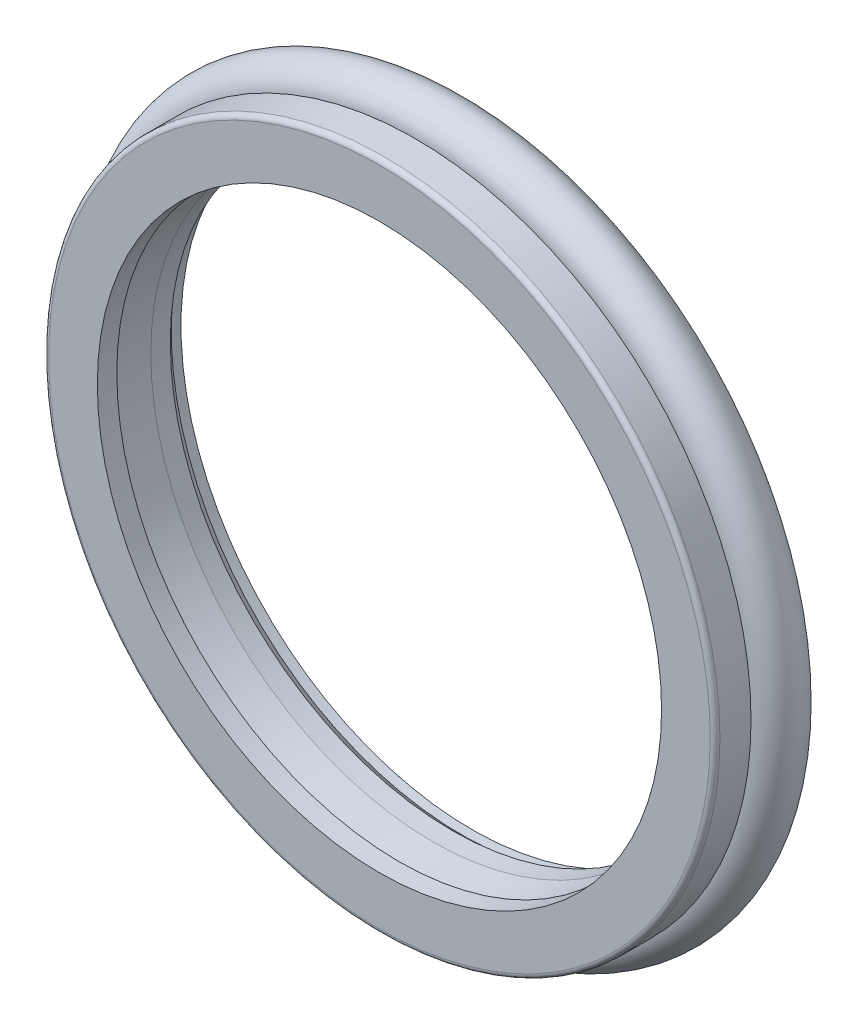
SolidWorks part; units mm, degrees
material "PTFE+NBR"
ref_plane "Front Plane" through (0, 0, 0) normal (0, 0, 1) x (1, 0, 0)
ref_plane "Top Plane" through (0, 0, 0) normal (0, 1, 0) x (1, 0, 0)
ref_plane "Right Plane" through (0, 0, 0) normal (1, 0, 0) x (0, 0, -1)
sketch "Sketch1" plane through (0, 0, 0) normal (1, 0, 0) x (0, 0, -1)
  line L0 (0, 0) -> (11.2675, 0) construction
  line L1 (0.25, 17.25) -> (1.85, 17.25)
  line L2 (0, 17) -> (0, 14.5)
  line L3 (4.75, 15.75) -> (4.75, 14.95)
  line L4 (4.75, 14.95) -> (4.25, 14.95)
  line L5 (4.25, 14.95) -> (3.75, 14.5)
  line L6 (1, 14.7) -> (2.75, 14.5)
  line L7 (4.75, 15.75) -> (1.85, 15.75)
  line L8 (1.85, 15.75) -> (1.85, 17.25)
  line L9 (1, 14.7) -> (1, 14.5)
  line L10 (1, 14.5) -> (0, 14.5)
  line L11 (3.75, 14.5) -> (2.75, 14.5)
  arc A2 (0.25, 17.25) -> (0, 17) centre (0.25, 17) ccw
  circle A4 centre (3.3, 17.05) radius 1.3 construction
  point P8 (3.3, 15.75)
  dimension "D8" = 1
  dimension "D12" = 36.7
  dimension "D13" = 2.6
  dimension "D14" = 31.5
  dimension "D16" = 2.9
  dimension "D17" = 0.25
  dimension "D1" = 0.5
  dimension "D2" = 1
  dimension "D3" = 4.75
  dimension "D4" = 1
  dimension "D5" = 34.5
  dimension "D6" = 29
  dimension "D7" = 0.8
  dimension "D9" = 29
  dimension "D10" = 0.2
revolve "Revolve1" add sketch "Sketch1" angle 360 about L0
sketch "Sketch2" plane through (0, 0, 0) normal (1, 0, 0) x (0, 0, -1)
  line L2 (0, 0) -> (10.3771, 0) construction
  circle A0 centre (3.3, 17.05) radius 1.3
  dimension "D1" = 2.6
  dimension "D2" = 36.7
revolve "Revolve2" add sketch "Sketch2" angle 360 about L2
